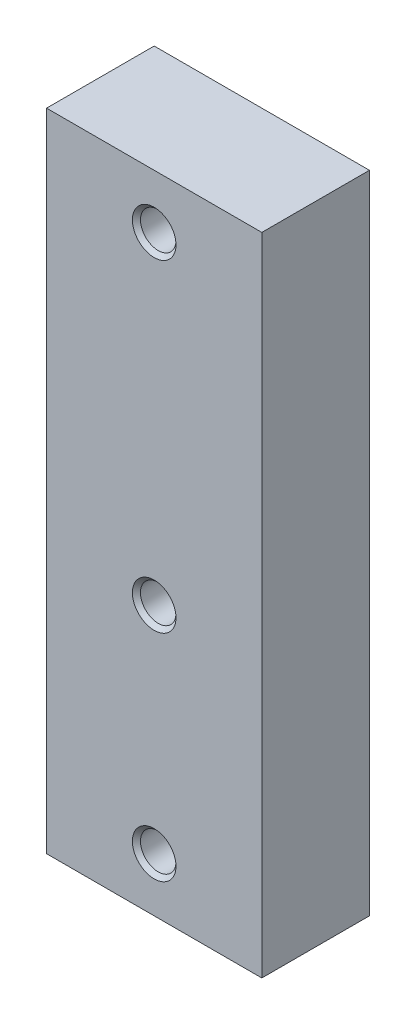
SolidWorks part; units mm, degrees
material "1.0037 (S235JR)"
ref_plane "Ebene vorne" through (0, 0, 0) normal (0, 0, 1) x (1, 0, 0)
ref_plane "Ebene oben" through (0, 0, 0) normal (0, 1, 0) x (1, 0, 0)
ref_plane "Ebene rechts" through (0, 0, 0) normal (1, 0, 0) x (0, 0, -1)
sketch "Skizze1" plane through (0, 0, 0) normal (0, 0, 1) x (1, 0, 0)
  line L1 (0, 0) -> (20, 0)
  line L2 (0, 0) -> (0, 60)
  line L3 (0, 60) -> (20, 60)
  line L4 (20, 0) -> (20, 60)
  dimension "D1" = 20
  dimension "D2" = 60
extrude "Aufsatz-Linear austragen1" add sketch "Skizze1" along normal blind 10
hole_wizard "M4x0.7 Gewindebohrung2" positions "Skizze6" profile "Skizze7" tap size "M4x0.7" standard "ANSI Metrisch" end condition through all
sketch "Skizze6" plane through (0, 0, 10) normal (0, 0, 1) x (1, 0, 0)
  line L0 (10, 60) -> (10, 0) construction
  line L1 (20, 60) -> (0, 60) construction
  line L2 (0, 0) -> (20, 0) construction
  point P2 (10, 55)
  point P6 (10, 25)
  point P15 (10, 5)
  dimension "D3" = 25
  dimension "D5" = 5
  dimension "D1" = 55
sketch "Skizze7" plane through (10, 55, 10) normal (1, 0, 0) x (0, -1, 0)
  line L0 (0, 0) -> (0, 10)
  line L1 (0, 10) -> (1.65, 10)
  line L2 (1.65, 10) -> (1.65, 0.375)
  line L3 (1.65, 0.375) -> (2.025, 0)
  line L5 (2.025, 0) -> (0, 0)
  line L6 (-1.65, 0.375) -> (-2.025, 0) construction
  line L11 (0, -6.35) -> (0, 107.95) construction
  dimension "Bohrerdurchmesser" = 3.3
  dimension "Bohrungstiefe" = 10
  dimension "Senkdurchmesser (Oben)" = 4.05
  dimension "Senkwinkel (Oben)" = 90
cosmetic thread "Bohrungsgewinde3"
cosmetic thread "Bohrungsgewinde5"
cosmetic thread "Bohrungsgewinde7"
hole_wizard "M4 Gewindebohrung1" positions "Skizze13" profile "Skizze12" tap size "M4" standard "DIN"
sketch "Skizze13" plane through (0, 0, 0) normal (0, -1, 0) x (-1, 0, 0)
  line L1 (-20, -10) -> (-20, 0) construction
  point P0 (-15, -5.1346)
  point P2 (-5, -5.1346)
  dimension "D1" = 10
  dimension "D2" = 5
cosmetic thread "Bohrungsgewinde8"
cosmetic thread "Bohrungsgewinde9"
sketch "Skizze12" plane through (15, 0, 5.1346) normal (1, 0, 0) x (0, 0, -1)
  line L0 (0, 0) -> (0, 30.9914)
  line L1 (0, 30.9914) -> (1.65, 30)
  line L2 (1.65, 30) -> (1.65, 0)
  line L5 (1.65, 0) -> (0, 0)
  line L10 (0, 30.9914) -> (-1.65, 30) construction
  line L11 (0, -6.35) -> (0, 107.95) construction
  dimension "Bohrerdurchmesser" = 3.3
  dimension "Bohrungstiefe" = 30
  dimension "Spitzenwinkel" = 118
equation "\"D1@Skizze6\"=\"D3@Skizze6\"+30"
